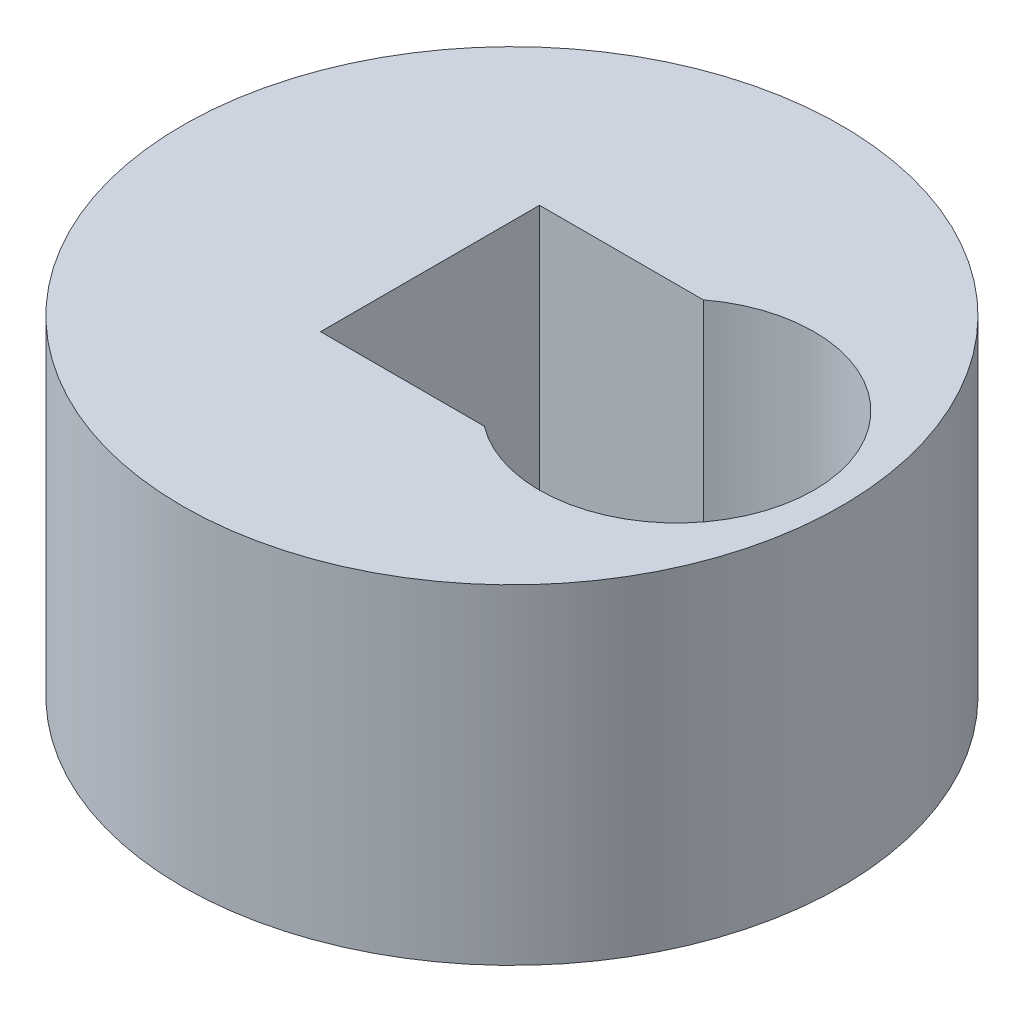
SolidWorks part; units mm, degrees
other "标注1"
sketch "草图3" plane through (-6, 6, 6) normal (-0.0088, 0.612, 0.7908) x (0.9999, 0, 0.0112)
other "标注2"
sketch "草图4" plane through (-6, 6, 6) normal (-0.0088, 0.612, 0.7908) x (0.9999, 0, 0.0112)
ref_plane "前视基准面" through (0, 0, 0) normal (0, 0, 1) x (1, 0, 0)
ref_plane "上视基准面" through (0, 0, 0) normal (0, 1, 0) x (1, 0, 0)
ref_plane "右视基准面" through (0, 0, 0) normal (1, 0, 0) x (0, 0, -1)
sketch "草图1" plane through (0, 0, 0) normal (0, 1, 0) x (1, 0, 0)
  line L0 (0, 0) -> (3, 0) construction
  circle A0 centre (0, 0) radius 6
  circle A3 centre (3, 0) radius 2.5
  dimension "D1" = 12
  dimension "D2" = 5
  dimension "D3" = 3
extrude "凸台-拉伸4" add sketch "草图1" along normal blind 6
sketch "草图2" plane through (0, 6, 0) normal (0, 1, 0) x (1, 0, 0)
  line L1 (-1.4909, 1.9932) -> (1.4909, 1.9932)
  line L2 (-1.4909, 1.9932) -> (-1.4909, -1.9932)
  line L3 (-1.4909, -1.9932) -> (1.4909, -1.9932)
  line L4 (1.4909, 1.9932) -> (1.4909, -1.9932)
  line L5 (-1.4909, 1.9932) -> (1.4909, -1.9932) construction
  line L6 (-1.4909, -1.9932) -> (1.4909, 1.9932) construction
  circle A0 centre (3, 0) radius 2.5 construction
  point P0 (0, 0)
extrude "切除-拉伸1" cut sketch "草图2" against normal blind 10
